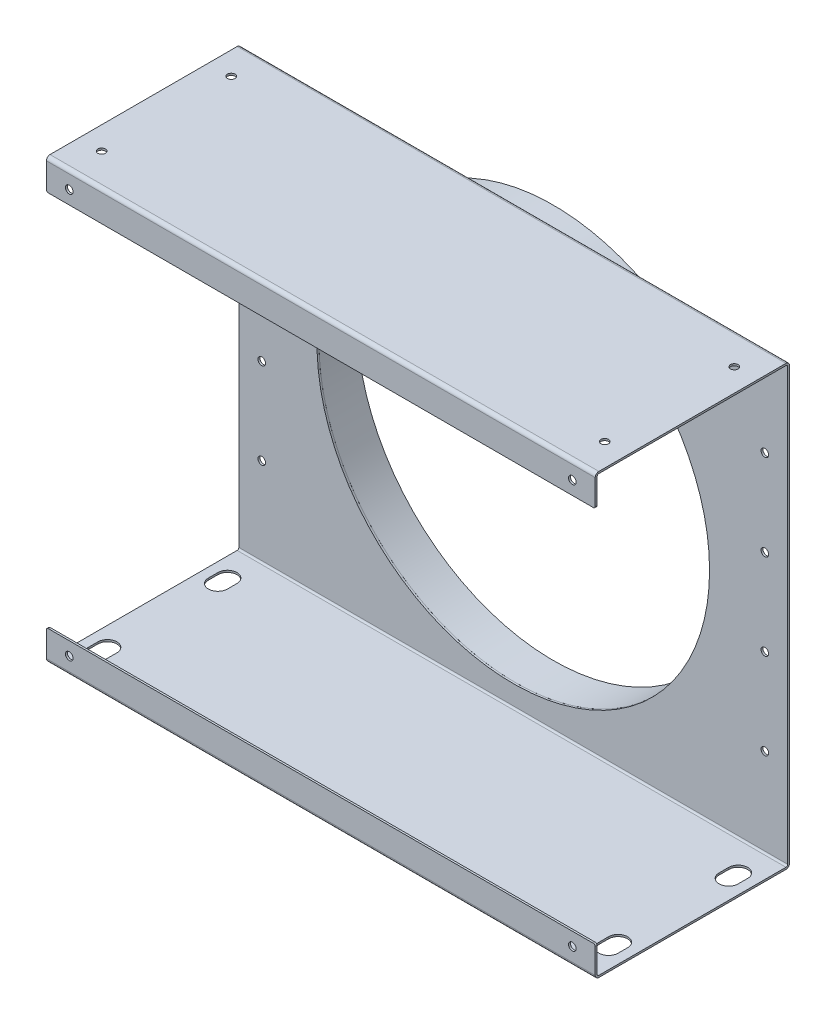
SolidWorks part; units mm, degrees
ref_plane "Спереди" through (0, 0, 0) normal (0, 0, 1) x (1, 0, 0)
ref_plane "Сверху" through (0, 0, 0) normal (0, 1, 0) x (1, 0, 0)
ref_plane "Справа" through (0, 0, 0) normal (1, 0, 0) x (0, 0, -1)
sketch "Эскиз1" plane through (0, 0, 0) normal (0, 0, 1) x (1, 0, 0)
  line L0 (288, 230) -> (288, 0)
  line L1 (0, 0) -> (0, 230)
  line L2 (0, 230) -> (288, 230)
  line L3 (288, 0) -> (0, 0)
  circle A0 centre (144, 115) radius 103
extrude "Бобышка-Вытянуть1" add sketch "Эскиз1" along normal blind 1
sketch "Эскиз2" plane through (0, 0, 1) normal (0, 0, 1) x (1, 0, 0)
  line L0 (0, 230) -> (288, 230)
  line L1 (288, 230) -> (288, 229)
  line L2 (288, 0) -> (288, 230) construction
  line L3 (288, 229) -> (0, 229)
  line L4 (0, 230) -> (0, 0) construction
  line L5 (0, 229) -> (0, 230)
  line L6 (288, 0) -> (0, 0)
  line L7 (0, 0) -> (0, 1)
  line L8 (0, 1) -> (288, 1)
  line L9 (288, 1) -> (288, 0)
extrude "Бобышка-Вытянуть2" add sketch "Эскиз2" along normal blind 101
fillet "Скругление1" radius 1.9 2 edges at (144, 0, 0) (144, 230, 0)
fillet "Скругление2" radius 0.9 2 edges at (144, 229, 1) (144, 1, 1)
sketch "Эскиз3" plane through (0, 229, 0) normal (0, -1, 0) x (1, 0, 0)
  line L0 (0, 102) -> (288, 102)
  line L1 (288, 102) -> (288, 101)
  line L2 (288, 102) -> (288, 1.9) construction
  line L3 (288, 101) -> (0, 101)
  line L4 (0, 102) -> (0, 1.9) construction
  line L5 (0, 101) -> (0, 102)
  dimension "D1" = 1
extrude "Бобышка-Вытянуть3" add sketch "Эскиз3" along normal blind 15
sketch "Эскиз4" plane through (0, 1, 0) normal (0, 1, 0) x (1, 0, 0)
  line L0 (0, -102) -> (288, -102)
  line L1 (288, -102) -> (288, -101)
  line L2 (288, -102) -> (288, -1.9) construction
  line L3 (288, -101) -> (0, -101)
  line L4 (0, -101) -> (0, -102)
extrude "Бобышка-Вытянуть4" add sketch "Эскиз4" along normal blind 15
fillet "Скругление3" radius 1.9 2 edges at (144, 0, 102) (144, 230, 102)
fillet "Скругление4" radius 0.9 2 edges at (144, 229, 101) (144, 1, 101)
sketch "Эскиз5" plane through (0, 0, 0) normal (0, 0, -1) x (-1, 0, 0)
  circle A0 centre (-144, 115) radius 103 construction
  circle A1 centre (-144, 115) radius 103
  circle A2 centre (-144, 115) radius 104
  dimension "D1" = 1
extrude "Бобышка-Вытянуть5" add sketch "Эскиз5" along normal blind 20 separate body
fillet "Скругление10" radius 1 4 edges at (288, 16, 101.5) (0, 16, 101.5) (0, 214, 101.5) (288, 214, 101.5)
sketch "Эскиз7" plane through (0, 230, 0) normal (0, 1, 0) x (1, 0, 0)
  line L0 (0, -98) -> (0, -4) construction
  line L1 (0, 0) -> (288, 0) construction
  line L2 (288, -102) -> (0, -102) construction
  line L3 (0, -100.1) -> (0, -1.9) construction
  line L4 (144, -102) -> (144, -15.0532) construction
  circle A0 centre (12, -17) radius 2
  circle A1 centre (12, -85) radius 2
  circle A2 centre (276, -85) radius 2
  circle A3 centre (276, -17) radius 2
  dimension "D1" = 4
  dimension "D2" = 4
  dimension "D3" = 12
  dimension "D4" = 17
  dimension "D5" = 17
  dimension "D6" = 12
extrude "Вырез-Вытянуть1" cut sketch "Эскиз7" against normal blind 30
sketch "Эскиз8" plane through (0, 0, 102) normal (0, 0, 1) x (1, 0, 0)
  line L0 (0, 4) -> (0, 226) construction
  line L1 (287, 214) -> (1, 214) construction
  line L2 (288, 215) -> (288, 228.1) construction
  circle A0 centre (12, 221) radius 2
  circle A1 centre (276, 221) radius 2
  dimension "D1" = 4
  dimension "D2" = 4
  dimension "D3" = 12
  dimension "D4" = 7
  dimension "D5" = 7
  dimension "D6" = 12
extrude "Вырез-Вытянуть2" cut sketch "Эскиз8" against normal blind 30
sketch "Эскиз9" plane through (0, 0, 102) normal (0, 0, 1) x (1, 0, 0)
  line L0 (1, 16) -> (287, 16) construction
  line L1 (0, 15) -> (0, 1.9) construction
  line L2 (288, 1.9) -> (288, 15) construction
  circle A0 centre (12, 9) radius 2
  circle A1 centre (276, 9) radius 2
  dimension "D1" = 4
  dimension "D4" = 4
  dimension "D2" = 7
  dimension "D3" = 12
  dimension "D5" = 12
  dimension "D6" = 7
extrude "Вырез-Вытянуть3" cut sketch "Эскиз9" against normal blind 30
sketch "Эскиз10" plane through (0, 0, 0) normal (0, 0, -1) x (-1, 0, 0)
  line L2 (0, 228.1) -> (-288, 228.1) construction
  line L3 (0, 228.1) -> (0, 1.9) construction
  circle A0 centre (-12, 182.9) radius 2
  circle A1 centre (-12, 137.7) radius 2
  circle A2 centre (-12, 47.3) radius 2
  circle A3 centre (-12, 92.5) radius 2
  circle A4 centre (-276, 92.5) radius 2
  circle A5 centre (-276, 47.3) radius 2
  circle A6 centre (-276, 137.7) radius 2
  circle A7 centre (-276, 182.9) radius 2
  dimension "D1" = 4
  dimension "D2" = 4
  dimension "D3" = 4
  dimension "D4" = 4
  dimension "D5" = 45.2
  dimension "D6" = 12
  dimension "D7" = 12
  dimension "D8" = 45.2
  dimension "D9" = 12
  dimension "D10" = 45.2
  dimension "D11" = 12
  dimension "D12" = 45.2
extrude "Вырез-Вытянуть4" cut sketch "Эскиз10" against normal blind 30
sketch "Эскиз11" plane through (0, 1, 0) normal (0, 1, 0) x (1, 0, 0)
  line L0 (5, -17) -> (5, -22) construction
  line L1 (15, -17) -> (15, -22) construction
  line L2 (5, -85) -> (5, -80) construction
  line L3 (15, -85) -> (15, -80) construction
  line L4 (283, -22) -> (283, -17) construction
  line L5 (273, -17) -> (273, -22) construction
  line L6 (283, -85) -> (283, -80) construction
  line L7 (273, -80) -> (273, -85) construction
  line L12 (5, -17) -> (5, -22)
  line L13 (15, -17) -> (15, -22)
  line L14 (5, -85) -> (5, -80)
  line L15 (15, -85) -> (15, -80)
  line L16 (283, -22) -> (283, -17)
  line L17 (273, -17) -> (273, -22)
  line L18 (283, -85) -> (283, -80)
  line L19 (273, -80) -> (273, -85)
  arc A0 (5, -22) -> (15, -22) centre (10, -22) ccw construction
  arc A1 (15, -17) -> (5, -17) centre (10, -17) ccw construction
  arc A2 (15, -80) -> (5, -80) centre (10, -80) ccw construction
  arc A3 (5, -85) -> (15, -85) centre (10, -85) ccw construction
  arc A6 (273, -22) -> (283, -22) centre (278, -22) ccw construction
  arc A7 (283, -17) -> (273, -17) centre (278, -17) ccw construction
  arc A8 (283, -80) -> (273, -80) centre (278, -80) ccw construction
  arc A9 (273, -85) -> (283, -85) centre (278, -85) ccw construction
  arc A10 (5, -22) -> (15, -22) centre (10, -22) ccw
  arc A11 (15, -17) -> (5, -17) centre (10, -17) ccw
  arc A12 (15, -80) -> (5, -80) centre (10, -80) ccw
  arc A13 (5, -85) -> (15, -85) centre (10, -85) ccw
  arc A14 (273, -22) -> (283, -22) centre (278, -22) ccw
  arc A15 (283, -17) -> (273, -17) centre (278, -17) ccw
  arc A16 (283, -80) -> (273, -80) centre (278, -80) ccw
  arc A17 (273, -85) -> (283, -85) centre (278, -85) ccw
extrude "Вырез-Вытянуть5" cut sketch "Эскиз11" against normal blind 10
